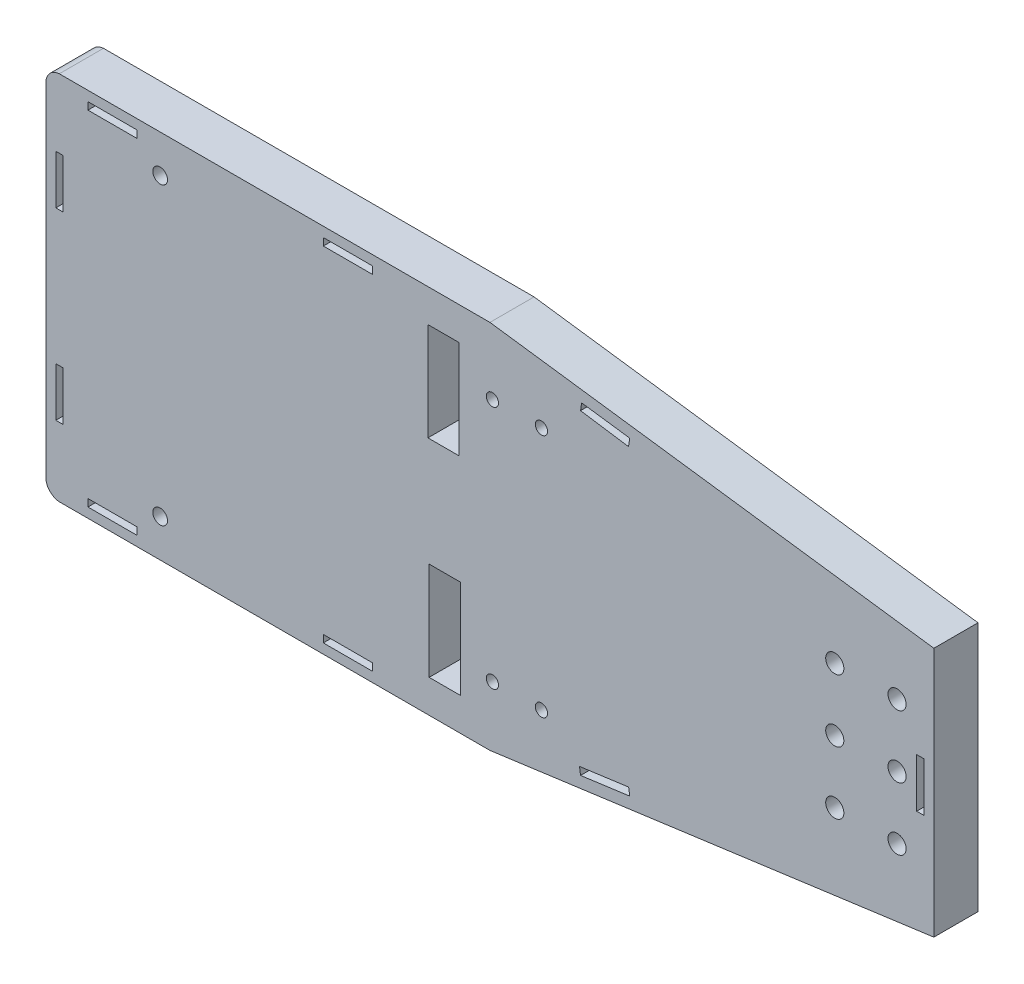
SolidWorks part; units mm, degrees
ref_plane "Front Plane" through (0, 0, 0) normal (0, 0, 1) x (1, 0, 0)
ref_plane "Top Plane" through (0, 0, 0) normal (0, 1, 0) x (1, 0, 0)
ref_plane "Right Plane" through (0, 0, 0) normal (1, 0, 0) x (0, 0, -1)
sketch "Sketch1" plane through (0, 0, 0) normal (0, 0, 1) x (1, 0, 0)
  line L1 (-90.5, -37.785) -> (90.5, -37.785)
  line L2 (-90.5, -37.785) -> (-90.5, 37.785)
  line L3 (-90.5, 37.785) -> (90.5, 37.785)
  line L4 (90.5, -37.785) -> (90.5, 37.785)
  line L5 (-90.5, -37.785) -> (90.5, 37.785) construction
  line L6 (-90.5, 37.785) -> (90.5, -37.785) construction
  point P0 (0, 0)
extrude "Boss-Extrude2" add sketch "Sketch1" along normal blind 9
sketch "Sketch6" plane through (0, 0, 9) normal (0, 0, 1) x (1, 0, 0)
  line L0 (-90.5, 0) -> (90.5, 0) construction
  line L1 (-90.5, 37.785) -> (-90.5, -37.785) construction
  line L2 (90.5, -37.785) -> (90.5, 37.785) construction
  line L3 (0, 37.785) -> (0, -37.785) construction
  line L4 (90.5, 37.785) -> (-90.5, 37.785) construction
  line L5 (-90.5, -37.785) -> (90.5, -37.785) construction
  line L6 (-90.5, 34.4318) -> (-90.5, -34.4318)
  line L7 (90.5, 25.5034) -> (90.5, -25.5034)
  line L8 (0, 37.785) -> (90.5, 25.5034)
  line L9 (0, -37.785) -> (90.5, -25.5034)
  line L10 (-17.18, 37.785) -> (-17.18, -37.785) construction
  line L11 (-81.9472, 34.285) -> (-71.9472, 34.285)
  line L12 (-88.5, 23.75) -> (-87, 23.75)
  line L13 (-88.5, 23.75) -> (-88.5, 13.75)
  line L14 (-88.5, 13.75) -> (-87, 13.75)
  line L15 (-87, 23.75) -> (-87, 13.75)
  line L16 (-88.5, -13.75) -> (-87, -13.75)
  line L17 (-88.5, -13.75) -> (-88.5, -23.75)
  line L18 (-88.5, -23.75) -> (-87, -23.75)
  line L19 (-87, -13.75) -> (-87, -23.75)
  line L20 (-33.9626, 34.285) -> (-33.9626, 35.785)
  line L21 (-33.9626, 34.285) -> (-23.9626, 34.285)
  line L22 (-33.9626, 35.785) -> (-23.9626, 35.785)
  line L23 (-23.9626, 34.285) -> (-23.9626, 35.785)
  line L24 (-71.9472, 34.285) -> (-71.9472, 35.785)
  line L25 (-81.9472, 34.285) -> (-81.9472, 35.785)
  line L26 (-81.9472, 35.785) -> (-71.9472, 35.785)
  line L27 (-81.9472, -34.285) -> (-71.9472, -34.285)
  line L28 (-71.9472, -35.785) -> (-71.9472, -34.285)
  line L29 (-81.9472, -35.785) -> (-71.9472, -35.785)
  line L30 (-81.9472, -35.785) -> (-81.9472, -34.285)
  line L31 (-33.9626, -35.785) -> (-23.9626, -35.785)
  line L32 (-33.9626, -35.785) -> (-33.9626, -34.285)
  line L33 (-23.9626, -35.785) -> (-23.9626, -34.285)
  line L34 (-33.9626, -34.285) -> (-23.9626, -34.285)
  line L35 (87, 4.9829) -> (87, -5.0171)
  line L36 (88.5, 4.9829) -> (88.5, -5.0171)
  line L37 (87, -5.0171) -> (88.5, -5.0171)
  line L38 (87, 4.9829) -> (88.5, 4.9829)
  line L39 (88.5, -0.0171) -> (87, -0.0171) construction
  line L40 (28.2601, 29.9768) -> (28.5018, 31.5992)
  line L41 (18.4768, 31.446) -> (28.2601, 29.9768)
  line L42 (18.4768, 31.446) -> (18.6996, 32.9294)
  line L43 (18.6996, 32.9294) -> (28.5018, 31.5992)
  line L44 (18.2709, -31.4771) -> (28.2794, -30.1189)
  line L45 (18.4726, -32.9635) -> (18.2709, -31.4771)
  line L46 (18.4726, -32.9635) -> (28.5018, -31.6025)
  line L47 (28.5018, -31.6025) -> (28.2794, -30.1189)
  line L48 (-87.3981, -37.785) -> (0, -37.785)
  line L49 (-87.3981, 37.785) -> (0, 37.785)
  line L51 (-12.639, 31.081) -> (-6.2709, 31.081)
  line L52 (-12.639, 31.081) -> (-12.639, 11.081)
  line L53 (-12.639, 11.081) -> (-6.2709, 11.081)
  line L54 (-6.2709, 31.081) -> (-6.2709, 11.081)
  line L55 (-12.3894, -11.08) -> (-6.0212, -11.08)
  line L56 (-12.3894, -11.08) -> (-12.3894, -31.08)
  line L57 (-12.3894, -31.08) -> (-6.0212, -31.08)
  line L58 (-6.0212, -11.08) -> (-6.0212, -31.08)
  arc A0 (-87.3981, 37.785) -> (-90.5, 34.4318) centre (-87.5923, 34.8533) ccw
  arc A1 (-90.5, -34.4318) -> (-87.3981, -37.785) centre (-87.5923, -34.8533) ccw
  circle A2 centre (-67.23, 30.095) radius 1.5
  circle A3 centre (-67.23, -30.095) radius 1.5
  circle A8 centre (0.5048, 24.4) radius 1.25
  circle A9 centre (10.5048, 24.4) radius 1.25
  circle A10 centre (10.5048, -25.4) radius 1.25
  circle A11 centre (0.5048, -25.4) radius 1.25
  circle A12 centre (83, -12.7534) radius 1.85
  circle A13 centre (83, 12.7534) radius 1.85
  circle A14 centre (83, 0) radius 1.85
  circle A15 centre (70.3, 12.7534) radius 1.85
  circle A16 centre (70.3, 0) radius 1.85
  circle A17 centre (70.3, -12.7534) radius 1.85
  point P21 (90.5, 0)
  point P77 (-86.8439, -37.785)
  point P84 (62.3573, -12.7534)
  point P85 (69.2022, 12.7534)
  point P90 (69.5247, -12.7534)
  point P91 (0, 0)
  point P92 (-90.5, -35.0466)
  point P93 (-87.3981, -37.785)
  point P94 (0, 0)
  point P95 (0, 0)
  line M4 (90.5, -37.785) -> (90.5, 37.785)
  line M5 (90.5, 37.785) -> (-90.5, 37.785)
  line M6 (-90.5, 37.785) -> (-90.5, -37.785)
  line M7 (-90.5, -37.785) -> (90.5, -37.785)
extrude "Cut-Extrude7" cut sketch "Sketch6" against normal blind 9 contours L9 M7 M4 | L8 M5 M4 | L38 L35 L37 L36 | A14 | A12 | A17 | A16 | A15 | A13 | L43 L42 L41 L40 | A9 | A8 | L54 L51 L52 L53 | L58 L55 L56 L57 | A11 | A10 | L46 L47 L44 L45 | L21 L23 L22 L20 | L26 L25 L11 L24 | A2 | A0 M5 M6 | L15 L12 L13 L14 | L19 L16 L17 L18 | A1 M6 M7 | L30 L29 L28 L27 | A3 | L34 L32 L31 L33
